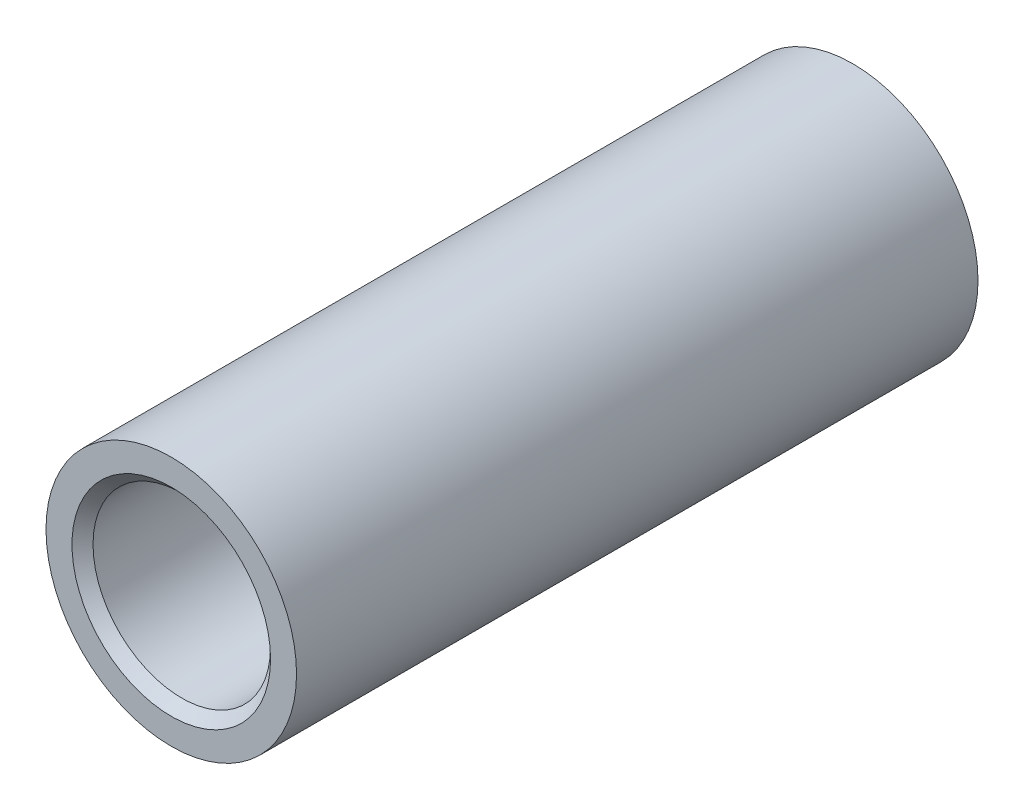
SolidWorks part; units mm, degrees
ref_plane "Front Plane" through (0, 0, 0) normal (0, 0, 1) x (1, 0, 0)
ref_plane "Top Plane" through (0, 0, 0) normal (0, 1, 0) x (1, 0, 0)
ref_plane "Right Plane" through (0, 0, 0) normal (1, 0, 0) x (0, 0, -1)
sketch "Sketch1" plane through (0, 0, 0) normal (0, 0, 1) x (1, 0, 0)
  circle A0 centre (0, 0) radius 3.375
  circle A1 centre (0, 0) radius 4.7625
  dimension "D1" = 6.75
  dimension "D2" = 9.525
extrude "Boss-Extrude1" add sketch "Sketch1" along normal blind 25.908
chamfer "Chamfer1" distance 0.4 angle 45 2 edges at (3.375, 0, 0) (3.375, 0, 25.908)
